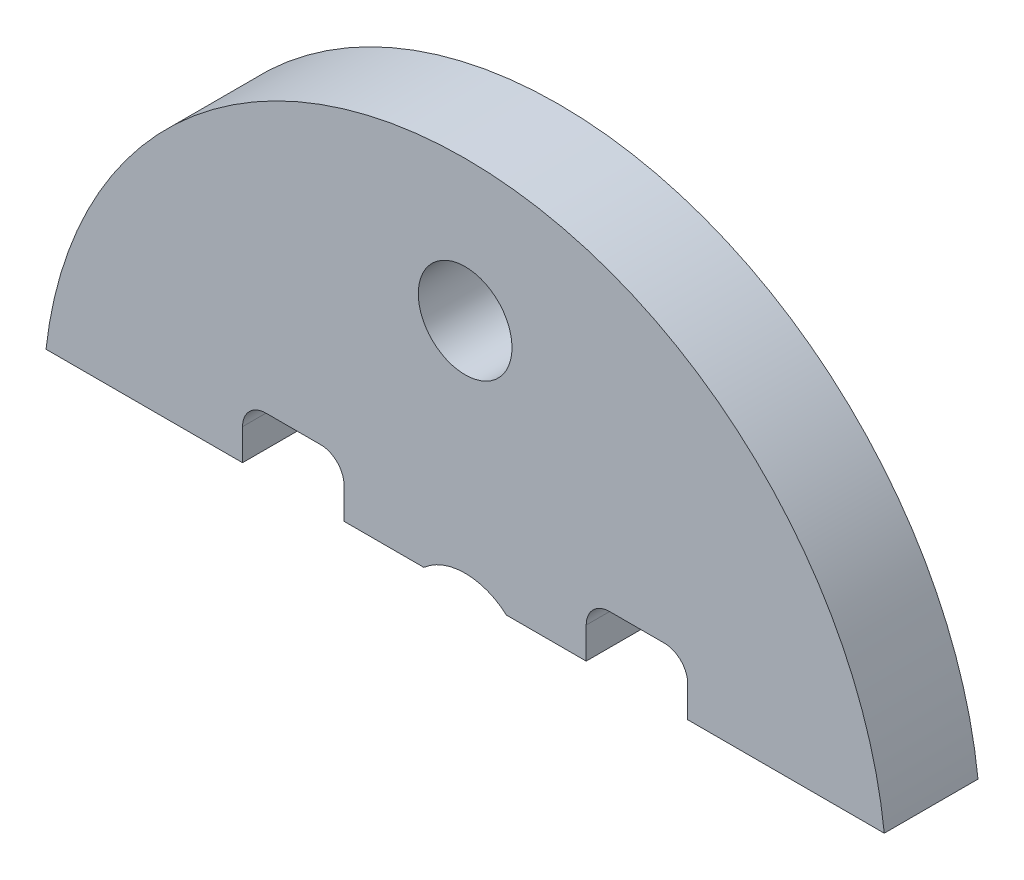
SolidWorks part; units mm, degrees
ref_plane "Alzado" through (0, 0, 0) normal (0, 0, 1) x (1, 0, 0)
ref_plane "Planta" through (0, 0, 0) normal (0, 1, 0) x (1, 0, 0)
ref_plane "Vista lateral" through (0, 0, 0) normal (1, 0, 0) x (0, 0, -1)
sketch "Model" plane through (0, 0, 0) normal (0, 0, 1) x (1, 0, 0)
  line L0 (21.2948, 286.1269) -> (18.7427, 286.1269)
  line L1 (26.4927, 286.1269) -> (23.9406, 286.1269)
  line L2 (36.0341, 286.1269) -> (29.7427, 286.1269)
  line L3 (29.7427, 286.1269) -> (29.7427, 287.1269)
  line L4 (26.4927, 287.1269) -> (26.4927, 286.1269)
  line L5 (18.7427, 287.1269) -> (18.7427, 286.1269)
  line L6 (15.4927, 286.1269) -> (15.4927, 287.1269)
  line L7 (15.4927, 286.1269) -> (9.2013, 286.1269)
  line L8 (16.2427, 287.8769) -> (17.9927, 287.8769)
  line L9 (28.9927, 287.8769) -> (27.2427, 287.8769)
  arc A0 (23.9406, 286.1269) -> (21.2948, 286.1269) centre (22.6177, 284.6269) ccw
  circle A1 centre (22.6177, 293.6269) radius 1.5
  arc A2 (16.2427, 287.8769) -> (15.4927, 287.1269) centre (16.2427, 287.1269) ccw
  arc A3 (18.7427, 287.1269) -> (17.9927, 287.8769) centre (17.9927, 287.1269) ccw
  arc A4 (29.7427, 287.1269) -> (28.9927, 287.8769) centre (28.9927, 287.1269) ccw
  arc A5 (27.2427, 287.8769) -> (26.4927, 287.1269) centre (27.2427, 287.1269) ccw
  arc A6 (36.0341, 286.1269) -> (9.2013, 286.1269) centre (22.6177, 284.6269) ccw
extrude "Saliente-Extruir1" add sketch "Model" along normal blind 3
